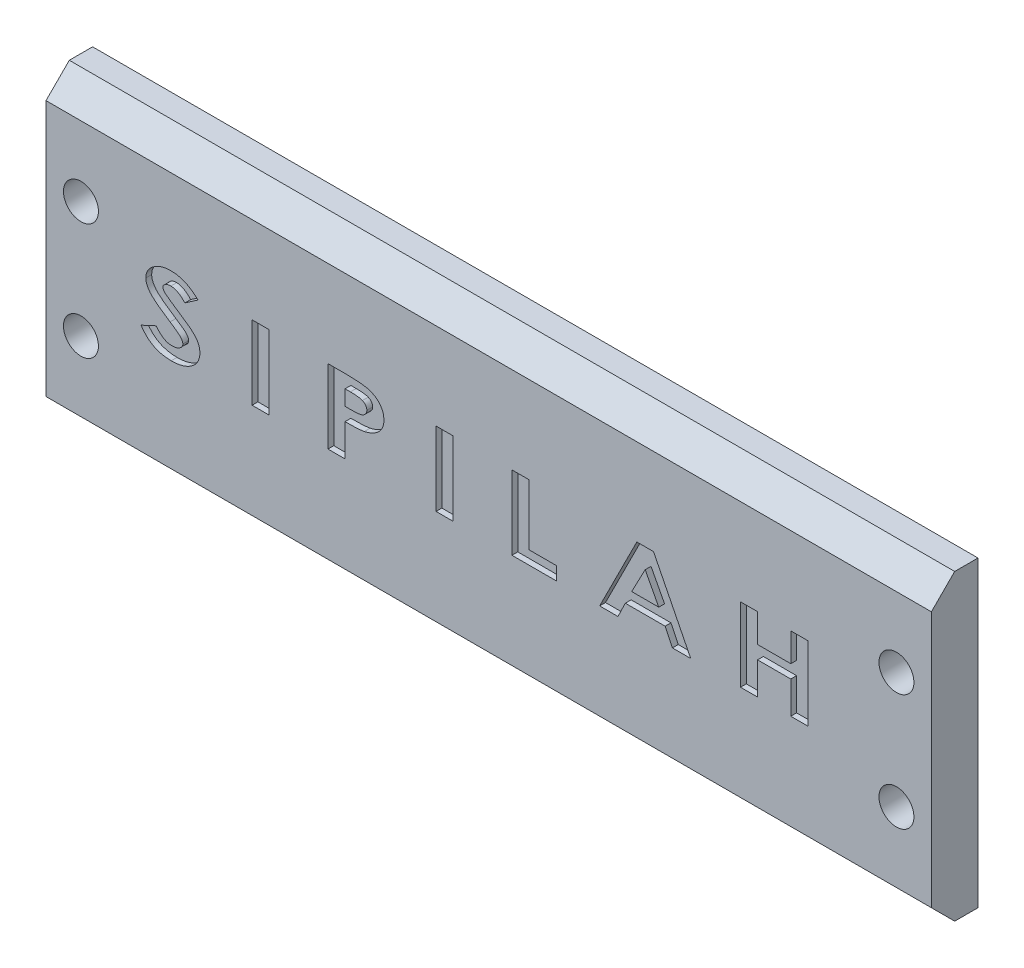
SolidWorks part; units mm, degrees
ref_plane "Front Plane" through (0, 0, 0) normal (0, 0, 1) x (1, 0, 0)
ref_plane "Top Plane" through (0, 0, 0) normal (0, 1, 0) x (1, 0, 0)
ref_plane "Right Plane" through (0, 0, 0) normal (1, 0, 0) x (0, 0, -1)
sketch "Sketch1" plane through (0, 0, 0) normal (0, 0, 1) x (1, 0, 0)
  line L1 (-38, 13) -> (38, 13)
  line L2 (-38, 13) -> (-38, -13)
  line L3 (-38, -13) -> (38, -13)
  line L4 (38, 13) -> (38, -13)
  line L5 (-38, 13) -> (38, -13) construction
  line L6 (-38, -13) -> (38, 13) construction
  point P0 (0, 0)
  dimension "D1" = 76
  dimension "D2" = 26
extrude "Boss-Extrude1" add sketch "Sketch1" along normal blind 4
sketch "Sketch2" plane through (0, 0, 4) normal (0, 0, 1) x (1, 0, 0)
  line L0 (0, 13) -> (0, -13) construction
  line L1 (38, 13) -> (-38, 13) construction
  line L2 (-38, -13) -> (38, -13) construction
  line L3 (-38, -2.8) -> (38, -2.8) construction
  line L4 (-38, 13) -> (-38, -13) construction
  line L5 (38, -13) -> (38, 13) construction
  text T0 "<b>S I P I L A H </b>" font "Century Gothic" height in points 24
  dimension "D1" = 2.8
  dimension "D2" = 13
extrude "Cut-Extrude1" cut sketch "Sketch2" against normal blind 0.5
sketch "Sketch3" plane through (0, 0, 4) normal (0, 0, 1) x (1, 0, 0)
  line L0 (38, 13) -> (-38, 13) construction
  line L2 (-35, 5) -> (-35, -5) construction
  line L3 (-38, 13) -> (-38, -13) construction
  line L4 (0, 13) -> (0, 7.478) construction
  circle A0 centre (-35, 5) radius 1.5
  circle A1 centre (-35, -5) radius 1.5
  circle A2 centre (35, -5) radius 1.5
  circle A3 centre (35, 5) radius 1.5
  dimension "D1" = 3
  dimension "D2" = 10
  dimension "D3" = 8
  dimension "D4" = 3
extrude "Cut-Extrude2" cut sketch "Sketch3" against normal through all
chamfer "Chamfer1" distance 2 angle 45 2 edges at (0, -13, 4) (0, 13, 4)
